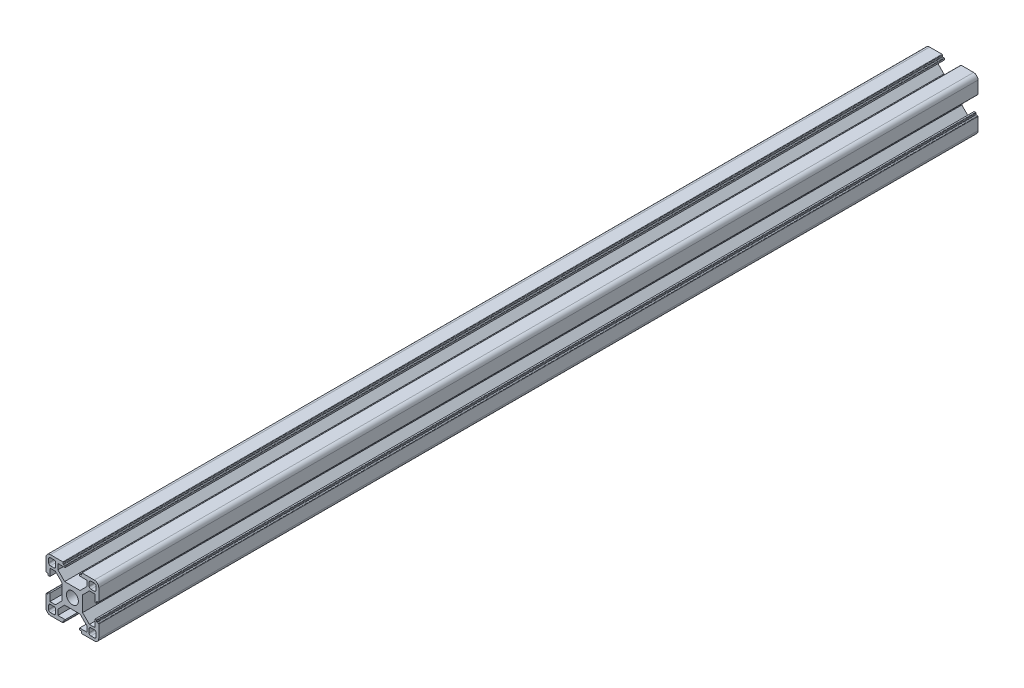
SolidWorks part; units mm, degrees
ref_plane "Front Plane" through (0, 0, 0) normal (0, 0, 1) x (1, 0, 0)
ref_plane "Top Plane" through (0, 0, 0) normal (0, 1, 0) x (1, 0, 0)
ref_plane "Right Plane" through (0, 0, 0) normal (1, 0, 0) x (0, 0, -1)
sketch "Sketch1" plane through (0, 0, 0) normal (0, 0, 1) x (1, 0, 0)
  line L0 (0, -5.8) -> (0, 5.8) construction
  line L1 (0, 0) -> (-15, 15) construction
  line L2 (-15, 15) -> (-5.2, 15)
  line L3 (-5.2, 15) -> (-5.2, 13.8083)
  line L4 (-5.2, 13.8083) -> (-4.1, 13.8083)
  line L5 (-4.1, 13.8083) -> (-4.1, 12.8)
  line L6 (-4.1, 12.8) -> (-8.25, 12.8)
  line L7 (-8.25, 12.8) -> (-8.25, 9.6642)
  line L8 (-8.25, 9.6642) -> (-4.3858, 5.8)
  line L9 (-4.3858, 5.8) -> (4.3858, 5.8)
  line L10 (-5.8, 4.3858) -> (-5.8, -4.3858)
  line L11 (-9.6642, 8.25) -> (-5.8, 4.3858)
  line L12 (-12.8, 8.25) -> (-9.6642, 8.25)
  line L13 (-12.8, 4.1) -> (-12.8, 8.25)
  line L14 (-13.8083, 4.1) -> (-12.8, 4.1)
  line L15 (-13.8083, 5.2) -> (-13.8083, 4.1)
  line L16 (-15, 5.2) -> (-13.8083, 5.2)
  line L17 (-15, 15) -> (-15, 5.2)
  line L18 (0, 0) -> (15, 15) construction
  line L19 (15, 15) -> (15, 5.2)
  line L20 (15, 5.2) -> (13.8083, 5.2)
  line L21 (13.8083, 5.2) -> (13.8083, 4.1)
  line L22 (13.8083, 4.1) -> (12.8, 4.1)
  line L23 (12.8, 4.1) -> (12.8, 8.25)
  line L24 (12.8, 8.25) -> (9.6642, 8.25)
  line L25 (9.6642, 8.25) -> (5.8, 4.3858)
  line L26 (5.8, 4.3858) -> (5.8, -4.3858)
  line L27 (8.25, 9.6642) -> (4.3858, 5.8)
  line L28 (8.25, 12.8) -> (8.25, 9.6642)
  line L29 (4.1, 12.8) -> (8.25, 12.8)
  line L30 (4.1, 13.8083) -> (4.1, 12.8)
  line L31 (5.2, 13.8083) -> (4.1, 13.8083)
  line L32 (5.2, 15) -> (5.2, 13.8083)
  line L33 (15, 15) -> (5.2, 15)
  line L34 (0, 0) -> (3.5826, 0) construction
  line L35 (0, 0) -> (15, -15) construction
  line L36 (0, 0) -> (-15, -15) construction
  line L37 (15, -15) -> (5.2, -15)
  line L38 (5.2, -15) -> (5.2, -13.8083)
  line L39 (5.2, -13.8083) -> (4.1, -13.8083)
  line L40 (4.1, -13.8083) -> (4.1, -12.8)
  line L41 (4.1, -12.8) -> (8.25, -12.8)
  line L42 (8.25, -12.8) -> (8.25, -9.6642)
  line L43 (8.25, -9.6642) -> (4.3858, -5.8)
  line L44 (9.6642, -8.25) -> (5.8, -4.3858)
  line L45 (12.8, -8.25) -> (9.6642, -8.25)
  line L46 (12.8, -4.1) -> (12.8, -8.25)
  line L47 (13.8083, -4.1) -> (12.8, -4.1)
  line L48 (13.8083, -5.2) -> (13.8083, -4.1)
  line L49 (15, -5.2) -> (13.8083, -5.2)
  line L50 (15, -15) -> (15, -5.2)
  line L51 (-15, -15) -> (-15, -5.2)
  line L52 (-15, -5.2) -> (-13.8083, -5.2)
  line L53 (-13.8083, -5.2) -> (-13.8083, -4.1)
  line L54 (-13.8083, -4.1) -> (-12.8, -4.1)
  line L55 (-12.8, -4.1) -> (-12.8, -8.25)
  line L56 (-12.8, -8.25) -> (-9.6642, -8.25)
  line L57 (-9.6642, -8.25) -> (-5.8, -4.3858)
  line L58 (-4.3858, -5.8) -> (4.3858, -5.8)
  line L59 (-8.25, -9.6642) -> (-4.3858, -5.8)
  line L60 (-8.25, -12.8) -> (-8.25, -9.6642)
  line L61 (-4.1, -12.8) -> (-8.25, -12.8)
  line L62 (-4.1, -13.8083) -> (-4.1, -12.8)
  line L63 (-5.2, -13.8083) -> (-4.1, -13.8083)
  line L64 (-5.2, -15) -> (-5.2, -13.8083)
  line L65 (-15, -15) -> (-5.2, -15)
  point P30 (0, 5.8)
  point P48 (5.8, 0)
  point P61 (-5.8, 0)
  dimension "D2" = 15
  dimension "D3" = 1
  dimension "D4" = 4.1
  dimension "D5" = 5.2
  dimension "D6" = 2.2
  dimension "D7" = 8.25
  dimension "D8" = 9.2
extrude "Boss-Extrude1" add sketch "Sketch1" along normal blind 250
sketch "Sketch2" plane through (0, 0, 250) normal (0, 0, 1) x (1, 0, 0)
  line L0 (0, 0) -> (0, 17.0054) construction
  line L1 (0, 0) -> (20.7717, 0) construction
  line L2 (-5.2, 15) -> (-15, 15) construction
  line L3 (-12.5, 13.5) -> (-10.5, 13.5)
  line L4 (-13.5, 12.5) -> (-13.5, 10.5)
  line L5 (-12.5, 9.5) -> (-10.5, 9.5)
  line L6 (-9.5, 12.5) -> (-9.5, 10.5)
  line L7 (-13.5, 13.5) -> (-9.5, 9.5) construction
  line L8 (-13.5, 9.5) -> (-9.5, 13.5) construction
  line L9 (-15, 15) -> (-15, 5.2) construction
  line L10 (13.5, 9.5) -> (9.5, 13.5) construction
  line L11 (13.5, 13.5) -> (9.5, 9.5) construction
  line L12 (9.5, 12.5) -> (9.5, 10.5)
  line L13 (12.5, 9.5) -> (10.5, 9.5)
  line L14 (13.5, 12.5) -> (13.5, 10.5)
  line L15 (12.5, 13.5) -> (10.5, 13.5)
  line L16 (13.5, -13.5) -> (9.5, -9.5) construction
  line L17 (13.5, -9.5) -> (9.5, -13.5) construction
  line L18 (-13.5, -9.5) -> (-9.5, -13.5) construction
  line L19 (-13.5, -13.5) -> (-9.5, -9.5) construction
  line L20 (12.5, -13.5) -> (10.5, -13.5)
  line L21 (13.5, -12.5) -> (13.5, -10.5)
  line L22 (12.5, -9.5) -> (10.5, -9.5)
  line L23 (9.5, -12.5) -> (9.5, -10.5)
  line L24 (-9.5, -12.5) -> (-9.5, -10.5)
  line L25 (-12.5, -9.5) -> (-10.5, -9.5)
  line L26 (-13.5, -12.5) -> (-13.5, -10.5)
  line L27 (-12.5, -13.5) -> (-10.5, -13.5)
  arc A0 (-12.5, 13.5) -> (-13.5, 12.5) centre (-12.5, 12.5) ccw
  arc A1 (-13.5, 10.5) -> (-12.5, 9.5) centre (-12.5, 10.5) ccw
  arc A2 (-10.5, 9.5) -> (-9.5, 10.5) centre (-10.5, 10.5) ccw
  arc A3 (-10.5, 13.5) -> (-9.5, 12.5) centre (-10.5, 12.5) cw
  arc A4 (10.5, 13.5) -> (9.5, 12.5) centre (10.5, 12.5) ccw
  arc A5 (10.5, 9.5) -> (9.5, 10.5) centre (10.5, 10.5) cw
  arc A6 (13.5, 10.5) -> (12.5, 9.5) centre (12.5, 10.5) cw
  arc A7 (12.5, 13.5) -> (13.5, 12.5) centre (12.5, 12.5) cw
  arc A8 (12.5, -13.5) -> (13.5, -12.5) centre (12.5, -12.5) ccw
  arc A9 (13.5, -10.5) -> (12.5, -9.5) centre (12.5, -10.5) ccw
  arc A10 (10.5, -9.5) -> (9.5, -10.5) centre (10.5, -10.5) ccw
  arc A11 (10.5, -13.5) -> (9.5, -12.5) centre (10.5, -12.5) cw
  arc A12 (-10.5, -13.5) -> (-9.5, -12.5) centre (-10.5, -12.5) ccw
  arc A13 (-10.5, -9.5) -> (-9.5, -10.5) centre (-10.5, -10.5) cw
  arc A14 (-13.5, -10.5) -> (-12.5, -9.5) centre (-12.5, -10.5) cw
  arc A15 (-12.5, -13.5) -> (-13.5, -12.5) centre (-12.5, -12.5) cw
  circle A16 centre (0, 0) radius 3.4
  point P3 (-11.5, 11.5)
  point P41 (11.5, 11.5)
  point P74 (11.5, -11.5)
  point P75 (-11.5, -11.5)
  dimension "D5" = 1
  dimension "D6" = 6.8
  dimension "D1" = 1.5
  dimension "D2" = 1.5
  dimension "D3" = 4
  dimension "D4" = 4
extrude "Cut-Extrude1" cut sketch "Sketch2" against normal through all
fillet "Fillet1" radius 2.5 4 edges at (-15, -15, 125) (15, -15, 125) (15, 15, 125) (-15, 15, 125)
fillet "Fillet2" radius 0.25 24 edges at (-13.8083, 5.2, 125) (-13.8083, 4.1, 125) (-15, 5.2, 125) (-13.8083, -4.1, 125) (-13.8083, -5.2, 125) (-15, -5.2, 125) (-5.2, -15, 125) (-5.2, -13.8083, 125) (-4.1, -13.8083, 125) (4.1, -13.8083, 125) (5.2, -13.8083, 125) (5.2, -15, 125) (13.8083, -5.2, 125) (13.8083, -4.1, 125) (15, -5.2, 125) (13.8083, 4.1, 125) (13.8083, 5.2, 125) (15, 5.2, 125) (-4.1, 13.8083, 125) (-5.2, 13.8083, 125) (4.1, 13.8083, 125) (5.2, 13.8083, 125) (5.2, 15, 125) (-5.2, 15, 125)
sketch "Sketch3" plane through (0, 0, 0) normal (0, 0, -1) x (-1, 0, 0)
  line L0 (-12.5, 13.5) -> (-10.5, 13.5) construction
  line L1 (-10.5, 9.5) -> (-12.5, 9.5) construction
  line L2 (-9.5, 12.5) -> (-9.5, 10.5) construction
  line L3 (-13.5, 10.5) -> (-13.5, 12.5) construction
  line L4 (-9.5, 12.5) -> (-9.5, 10.5)
  line L5 (-12.5, 13.5) -> (-10.5, 13.5)
  line L6 (-13.5, 10.5) -> (-13.5, 12.5)
  line L7 (-10.5, 9.5) -> (-12.5, 9.5)
  line L8 (10.5, 13.5) -> (12.5, 13.5) construction
  line L9 (9.5, 10.5) -> (9.5, 12.5) construction
  line L10 (13.5, 12.5) -> (13.5, 10.5) construction
  line L11 (12.5, 9.5) -> (10.5, 9.5) construction
  line L12 (12.5, 9.5) -> (10.5, 9.5)
  line L13 (13.5, 12.5) -> (13.5, 10.5)
  line L14 (9.5, 10.5) -> (9.5, 12.5)
  line L15 (10.5, 13.5) -> (12.5, 13.5)
  line L16 (9.5, -12.5) -> (9.5, -10.5) construction
  line L17 (12.5, -13.5) -> (10.5, -13.5) construction
  line L18 (13.5, -10.5) -> (13.5, -12.5) construction
  line L19 (10.5, -9.5) -> (12.5, -9.5) construction
  line L20 (9.5, -12.5) -> (9.5, -10.5)
  line L21 (12.5, -13.5) -> (10.5, -13.5)
  line L22 (13.5, -10.5) -> (13.5, -12.5)
  line L23 (10.5, -9.5) -> (12.5, -9.5)
  line L24 (-9.5, -10.5) -> (-9.5, -12.5) construction
  line L25 (-10.5, -13.5) -> (-12.5, -13.5) construction
  line L26 (-13.5, -12.5) -> (-13.5, -10.5) construction
  line L27 (-12.5, -9.5) -> (-10.5, -9.5) construction
  line L28 (-9.5, -10.5) -> (-9.5, -12.5)
  line L29 (-10.5, -13.5) -> (-12.5, -13.5)
  line L30 (-13.5, -12.5) -> (-13.5, -10.5)
  line L31 (-12.5, -9.5) -> (-10.5, -9.5)
  line L60 (12.8, 4.1) -> (13.5583, 4.1)
  line L61 (13.8083, 4.35) -> (13.8083, 4.95)
  line L62 (14.0583, 5.2) -> (14.75, 5.2)
  line L63 (15, 5.45) -> (15, 12.5)
  line L64 (12.5, 15) -> (5.45, 15)
  line L65 (5.2, 14.75) -> (5.2, 14.0583)
  line L66 (4.95, 13.8083) -> (4.35, 13.8083)
  line L67 (4.1, 13.5583) -> (4.1, 12.8)
  line L68 (4.1, 12.8) -> (8.25, 12.8)
  line L69 (8.25, 12.8) -> (8.25, 9.6642)
  line L70 (8.25, 9.6642) -> (4.3858, 5.8)
  line L71 (4.3858, 5.8) -> (-4.3858, 5.8)
  line L72 (-4.3858, 5.8) -> (-8.25, 9.6642)
  line L73 (-8.25, 9.6642) -> (-8.25, 12.8)
  line L74 (-8.25, 12.8) -> (-4.1, 12.8)
  line L75 (-4.1, 12.8) -> (-4.1, 13.5583)
  line L76 (-4.35, 13.8083) -> (-4.95, 13.8083)
  line L77 (-5.2, 14.0583) -> (-5.2, 14.75)
  line L78 (-5.45, 15) -> (-12.5, 15)
  line L79 (-15, 12.5) -> (-15, 5.45)
  line L80 (-14.75, 5.2) -> (-14.0583, 5.2)
  line L81 (-13.8083, 4.95) -> (-13.8083, 4.35)
  line L82 (-13.5583, 4.1) -> (-12.8, 4.1)
  line L83 (-12.8, 4.1) -> (-12.8, 8.25)
  line L84 (-12.8, 8.25) -> (-9.6642, 8.25)
  line L85 (-9.6642, 8.25) -> (-5.8, 4.3858)
  line L86 (-5.8, 4.3858) -> (-5.8, -4.3858)
  line L87 (-5.8, -4.3858) -> (-9.6642, -8.25)
  line L88 (-9.6642, -8.25) -> (-12.8, -8.25)
  line L89 (-12.8, -8.25) -> (-12.8, -4.1)
  line L90 (-12.8, -4.1) -> (-13.5583, -4.1)
  line L91 (-13.8083, -4.35) -> (-13.8083, -4.95)
  line L92 (-14.0583, -5.2) -> (-14.75, -5.2)
  line L93 (-15, -5.45) -> (-15, -12.5)
  line L94 (-12.5, -15) -> (-5.45, -15)
  line L95 (-5.2, -14.75) -> (-5.2, -14.0583)
  line L96 (-4.95, -13.8083) -> (-4.35, -13.8083)
  line L97 (-4.1, -13.5583) -> (-4.1, -12.8)
  line L98 (-4.1, -12.8) -> (-8.25, -12.8)
  line L99 (-8.25, -12.8) -> (-8.25, -9.6642)
  line L100 (-8.25, -9.6642) -> (-4.3858, -5.8)
  line L101 (-4.3858, -5.8) -> (4.3858, -5.8)
  line L102 (4.3858, -5.8) -> (8.25, -9.6642)
  line L103 (8.25, -9.6642) -> (8.25, -12.8)
  line L104 (8.25, -12.8) -> (4.1, -12.8)
  line L105 (4.1, -12.8) -> (4.1, -13.5583)
  line L106 (4.35, -13.8083) -> (4.95, -13.8083)
  line L107 (5.2, -14.0583) -> (5.2, -14.75)
  line L108 (5.45, -15) -> (12.5, -15)
  line L109 (15, -12.5) -> (15, -5.45)
  line L110 (14.75, -5.2) -> (14.0583, -5.2)
  line L111 (13.8083, -4.95) -> (13.8083, -4.35)
  line L112 (13.5583, -4.1) -> (12.8, -4.1)
  line L113 (12.8, -4.1) -> (12.8, -8.25)
  line L114 (12.8, -8.25) -> (9.6642, -8.25)
  line L115 (9.6642, -8.25) -> (5.8, -4.3858)
  line L116 (5.8, -4.3858) -> (5.8, 4.3858)
  line L117 (5.8, 4.3858) -> (9.6642, 8.25)
  line L118 (9.6642, 8.25) -> (12.8, 8.25)
  line L119 (12.8, 8.25) -> (12.8, 4.1)
  line L120 (12.8, 4.1) -> (13.5583, 4.1)
  line L121 (13.8083, 4.35) -> (13.8083, 4.95)
  line L122 (14.0583, 5.2) -> (14.75, 5.2)
  line L123 (15, 5.45) -> (15, 12.5)
  line L124 (12.5, 15) -> (5.45, 15)
  line L125 (5.2, 14.75) -> (5.2, 14.0583)
  line L126 (4.95, 13.8083) -> (4.35, 13.8083)
  line L127 (4.1, 13.5583) -> (4.1, 12.8)
  line L128 (4.1, 12.8) -> (8.25, 12.8)
  line L129 (8.25, 12.8) -> (8.25, 9.6642)
  line L130 (8.25, 9.6642) -> (4.3858, 5.8)
  line L131 (4.3858, 5.8) -> (-4.3858, 5.8)
  line L132 (-4.3858, 5.8) -> (-8.25, 9.6642)
  line L133 (-8.25, 9.6642) -> (-8.25, 12.8)
  line L134 (-8.25, 12.8) -> (-4.1, 12.8)
  line L135 (-4.1, 12.8) -> (-4.1, 13.5583)
  line L136 (-4.35, 13.8083) -> (-4.95, 13.8083)
  line L137 (-5.2, 14.0583) -> (-5.2, 14.75)
  line L138 (-5.45, 15) -> (-12.5, 15)
  line L139 (-15, 12.5) -> (-15, 5.45)
  line L140 (-14.75, 5.2) -> (-14.0583, 5.2)
  line L141 (-13.8083, 4.95) -> (-13.8083, 4.35)
  line L142 (-13.5583, 4.1) -> (-12.8, 4.1)
  line L143 (-12.8, 4.1) -> (-12.8, 8.25)
  line L144 (-12.8, 8.25) -> (-9.6642, 8.25)
  line L145 (-9.6642, 8.25) -> (-5.8, 4.3858)
  line L146 (-5.8, 4.3858) -> (-5.8, -4.3858)
  line L147 (-5.8, -4.3858) -> (-9.6642, -8.25)
  line L148 (-9.6642, -8.25) -> (-12.8, -8.25)
  line L149 (-12.8, -8.25) -> (-12.8, -4.1)
  line L150 (-12.8, -4.1) -> (-13.5583, -4.1)
  line L151 (-13.8083, -4.35) -> (-13.8083, -4.95)
  line L152 (-14.0583, -5.2) -> (-14.75, -5.2)
  line L153 (-15, -5.45) -> (-15, -12.5)
  line L154 (-12.5, -15) -> (-5.45, -15)
  line L155 (-5.2, -14.75) -> (-5.2, -14.0583)
  line L156 (-4.95, -13.8083) -> (-4.35, -13.8083)
  line L157 (-4.1, -13.5583) -> (-4.1, -12.8)
  line L158 (-4.1, -12.8) -> (-8.25, -12.8)
  line L159 (-8.25, -12.8) -> (-8.25, -9.6642)
  line L160 (-8.25, -9.6642) -> (-4.3858, -5.8)
  line L161 (-4.3858, -5.8) -> (4.3858, -5.8)
  line L162 (4.3858, -5.8) -> (8.25, -9.6642)
  line L163 (8.25, -9.6642) -> (8.25, -12.8)
  line L164 (8.25, -12.8) -> (4.1, -12.8)
  line L165 (4.1, -12.8) -> (4.1, -13.5583)
  line L166 (4.35, -13.8083) -> (4.95, -13.8083)
  line L167 (5.2, -14.0583) -> (5.2, -14.75)
  line L168 (5.45, -15) -> (12.5, -15)
  line L169 (15, -12.5) -> (15, -5.45)
  line L170 (14.75, -5.2) -> (14.0583, -5.2)
  line L171 (13.8083, -4.95) -> (13.8083, -4.35)
  line L172 (13.5583, -4.1) -> (12.8, -4.1)
  line L173 (12.8, -4.1) -> (12.8, -8.25)
  line L174 (12.8, -8.25) -> (9.6642, -8.25)
  line L175 (9.6642, -8.25) -> (5.8, -4.3858)
  line L176 (5.8, -4.3858) -> (5.8, 4.3858)
  line L177 (5.8, 4.3858) -> (9.6642, 8.25)
  line L178 (9.6642, 8.25) -> (12.8, 8.25)
  line L179 (12.8, 8.25) -> (12.8, 4.1)
  circle A0 centre (0, 0) radius 3.4 construction
  circle A1 centre (0, 0) radius 3.4
  arc A2 (-12.5, 13.5) -> (-13.5, 12.5) centre (-12.5, 12.5) ccw construction
  arc A3 (-9.5, 12.5) -> (-10.5, 13.5) centre (-10.5, 12.5) ccw construction
  arc A4 (-13.5, 10.5) -> (-12.5, 9.5) centre (-12.5, 10.5) ccw construction
  arc A5 (-10.5, 9.5) -> (-9.5, 10.5) centre (-10.5, 10.5) ccw construction
  arc A6 (-9.5, 12.5) -> (-10.5, 13.5) centre (-10.5, 12.5) ccw
  arc A7 (-12.5, 13.5) -> (-13.5, 12.5) centre (-12.5, 12.5) ccw
  arc A8 (-13.5, 10.5) -> (-12.5, 9.5) centre (-12.5, 10.5) ccw
  arc A9 (-10.5, 9.5) -> (-9.5, 10.5) centre (-10.5, 10.5) ccw
  arc A10 (13.5, 12.5) -> (12.5, 13.5) centre (12.5, 12.5) ccw construction
  arc A11 (10.5, 13.5) -> (9.5, 12.5) centre (10.5, 12.5) ccw construction
  arc A12 (12.5, 9.5) -> (13.5, 10.5) centre (12.5, 10.5) ccw construction
  arc A13 (9.5, 10.5) -> (10.5, 9.5) centre (10.5, 10.5) ccw construction
  arc A14 (9.5, 10.5) -> (10.5, 9.5) centre (10.5, 10.5) ccw
  arc A15 (12.5, 9.5) -> (13.5, 10.5) centre (12.5, 10.5) ccw
  arc A16 (10.5, 13.5) -> (9.5, 12.5) centre (10.5, 12.5) ccw
  arc A17 (13.5, 12.5) -> (12.5, 13.5) centre (12.5, 12.5) ccw
  arc A18 (10.5, -9.5) -> (9.5, -10.5) centre (10.5, -10.5) ccw construction
  arc A19 (9.5, -12.5) -> (10.5, -13.5) centre (10.5, -12.5) ccw construction
  arc A20 (12.5, -13.5) -> (13.5, -12.5) centre (12.5, -12.5) ccw construction
  arc A21 (13.5, -10.5) -> (12.5, -9.5) centre (12.5, -10.5) ccw construction
  arc A22 (10.5, -9.5) -> (9.5, -10.5) centre (10.5, -10.5) ccw
  arc A23 (9.5, -12.5) -> (10.5, -13.5) centre (10.5, -12.5) ccw
  arc A24 (12.5, -13.5) -> (13.5, -12.5) centre (12.5, -12.5) ccw
  arc A25 (13.5, -10.5) -> (12.5, -9.5) centre (12.5, -10.5) ccw
  arc A26 (-9.5, -10.5) -> (-10.5, -9.5) centre (-10.5, -10.5) ccw construction
  arc A27 (-10.5, -13.5) -> (-9.5, -12.5) centre (-10.5, -12.5) ccw construction
  arc A28 (13.5583, 4.1) -> (13.8083, 4.35) centre (13.5583, 4.35) ccw
  arc A29 (14.0583, 5.2) -> (13.8083, 4.95) centre (14.0583, 4.95) ccw
  arc A30 (14.75, 5.2) -> (15, 5.45) centre (14.75, 5.45) ccw
  arc A31 (15, 12.5) -> (12.5, 15) centre (12.5, 12.5) ccw
  arc A32 (5.45, 15) -> (5.2, 14.75) centre (5.45, 14.75) ccw
  arc A33 (4.95, 13.8083) -> (5.2, 14.0583) centre (4.95, 14.0583) ccw
  arc A34 (4.35, 13.8083) -> (4.1, 13.5583) centre (4.35, 13.5583) ccw
  arc A35 (-4.1, 13.5583) -> (-4.35, 13.8083) centre (-4.35, 13.5583) ccw
  arc A36 (-5.2, 14.0583) -> (-4.95, 13.8083) centre (-4.95, 14.0583) ccw
  arc A37 (-5.2, 14.75) -> (-5.45, 15) centre (-5.45, 14.75) ccw
  arc A38 (-12.5, 15) -> (-15, 12.5) centre (-12.5, 12.5) ccw
  arc A39 (-15, 5.45) -> (-14.75, 5.2) centre (-14.75, 5.45) ccw
  arc A40 (-13.8083, 4.95) -> (-14.0583, 5.2) centre (-14.0583, 4.95) ccw
  arc A41 (-13.8083, 4.35) -> (-13.5583, 4.1) centre (-13.5583, 4.35) ccw
  arc A42 (-13.5583, -4.1) -> (-13.8083, -4.35) centre (-13.5583, -4.35) ccw
  arc A43 (-14.0583, -5.2) -> (-13.8083, -4.95) centre (-14.0583, -4.95) ccw
  arc A44 (-14.75, -5.2) -> (-15, -5.45) centre (-14.75, -5.45) ccw
  arc A45 (-15, -12.5) -> (-12.5, -15) centre (-12.5, -12.5) ccw
  arc A46 (-5.45, -15) -> (-5.2, -14.75) centre (-5.45, -14.75) ccw
  arc A47 (-4.95, -13.8083) -> (-5.2, -14.0583) centre (-4.95, -14.0583) ccw
  arc A48 (-4.35, -13.8083) -> (-4.1, -13.5583) centre (-4.35, -13.5583) ccw
  arc A49 (4.1, -13.5583) -> (4.35, -13.8083) centre (4.35, -13.5583) ccw
  arc A50 (5.2, -14.0583) -> (4.95, -13.8083) centre (4.95, -14.0583) ccw
  arc A51 (5.2, -14.75) -> (5.45, -15) centre (5.45, -14.75) ccw
  arc A52 (12.5, -15) -> (15, -12.5) centre (12.5, -12.5) ccw
  arc A53 (15, -5.45) -> (14.75, -5.2) centre (14.75, -5.45) ccw
  arc A54 (13.8083, -4.95) -> (14.0583, -5.2) centre (14.0583, -4.95) ccw
  arc A55 (13.8083, -4.35) -> (13.5583, -4.1) centre (13.5583, -4.35) ccw
  arc A56 (13.5583, 4.1) -> (13.8083, 4.35) centre (13.5583, 4.35) ccw
  arc A57 (14.0583, 5.2) -> (13.8083, 4.95) centre (14.0583, 4.95) ccw
  arc A58 (14.75, 5.2) -> (15, 5.45) centre (14.75, 5.45) ccw
  arc A59 (15, 12.5) -> (12.5, 15) centre (12.5, 12.5) ccw
  arc A60 (5.45, 15) -> (5.2, 14.75) centre (5.45, 14.75) ccw
  arc A61 (4.95, 13.8083) -> (5.2, 14.0583) centre (4.95, 14.0583) ccw
  arc A62 (4.35, 13.8083) -> (4.1, 13.5583) centre (4.35, 13.5583) ccw
  arc A63 (-4.1, 13.5583) -> (-4.35, 13.8083) centre (-4.35, 13.5583) ccw
  arc A64 (-5.2, 14.0583) -> (-4.95, 13.8083) centre (-4.95, 14.0583) ccw
  arc A65 (-5.2, 14.75) -> (-5.45, 15) centre (-5.45, 14.75) ccw
  arc A66 (-12.5, 15) -> (-15, 12.5) centre (-12.5, 12.5) ccw
  arc A67 (-15, 5.45) -> (-14.75, 5.2) centre (-14.75, 5.45) ccw
  arc A68 (-13.8083, 4.95) -> (-14.0583, 5.2) centre (-14.0583, 4.95) ccw
  arc A69 (-13.8083, 4.35) -> (-13.5583, 4.1) centre (-13.5583, 4.35) ccw
  arc A70 (-13.5583, -4.1) -> (-13.8083, -4.35) centre (-13.5583, -4.35) ccw
  arc A71 (-14.0583, -5.2) -> (-13.8083, -4.95) centre (-14.0583, -4.95) ccw
  arc A72 (-14.75, -5.2) -> (-15, -5.45) centre (-14.75, -5.45) ccw
  arc A73 (-15, -12.5) -> (-12.5, -15) centre (-12.5, -12.5) ccw
  arc A74 (-5.45, -15) -> (-5.2, -14.75) centre (-5.45, -14.75) ccw
  arc A75 (-4.95, -13.8083) -> (-5.2, -14.0583) centre (-4.95, -14.0583) ccw
  arc A76 (-4.35, -13.8083) -> (-4.1, -13.5583) centre (-4.35, -13.5583) ccw
  arc A77 (4.1, -13.5583) -> (4.35, -13.8083) centre (4.35, -13.5583) ccw
  arc A78 (5.2, -14.0583) -> (4.95, -13.8083) centre (4.95, -14.0583) ccw
  arc A79 (5.2, -14.75) -> (5.45, -15) centre (5.45, -14.75) ccw
  arc A80 (12.5, -15) -> (15, -12.5) centre (12.5, -12.5) ccw
  arc A81 (15, -5.45) -> (14.75, -5.2) centre (14.75, -5.45) ccw
  arc A82 (13.8083, -4.95) -> (14.0583, -5.2) centre (14.0583, -4.95) ccw
  arc A83 (13.8083, -4.35) -> (13.5583, -4.1) centre (13.5583, -4.35) ccw
  arc A84 (-13.5, -12.5) -> (-12.5, -13.5) centre (-12.5, -12.5) ccw construction
  arc A85 (-12.5, -9.5) -> (-13.5, -10.5) centre (-12.5, -10.5) ccw construction
  arc A86 (-9.5, -10.5) -> (-10.5, -9.5) centre (-10.5, -10.5) ccw
  arc A87 (-10.5, -13.5) -> (-9.5, -12.5) centre (-10.5, -12.5) ccw
  arc A88 (-13.5, -12.5) -> (-12.5, -13.5) centre (-12.5, -12.5) ccw
  arc A89 (-12.5, -9.5) -> (-13.5, -10.5) centre (-12.5, -10.5) ccw
  dimension "D1" = 0
extrude "Boss-Extrude3" add sketch "Sketch3" along normal blind 250
